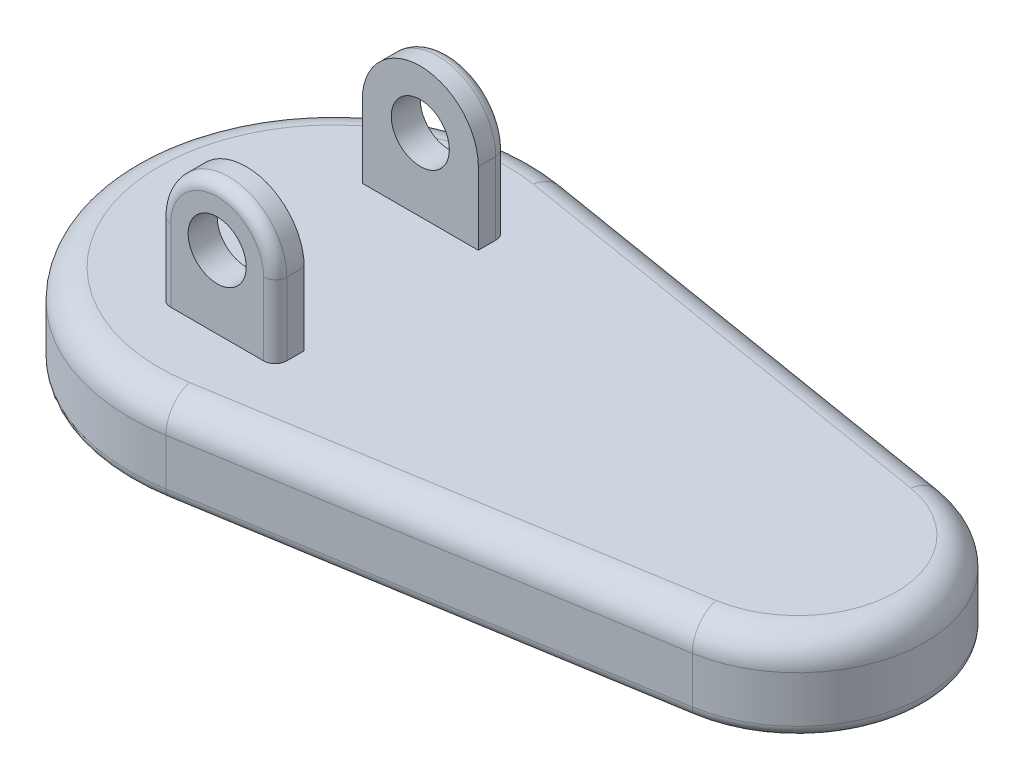
SolidWorks part; units mm, degrees
material "ABS"
ref_plane "Front Plane" through (0, 0, 0) normal (0, 0, 1) x (1, 0, 0)
ref_plane "Top Plane" through (0, 0, 0) normal (0, 1, 0) x (1, 0, 0)
ref_plane "Right Plane" through (0, 0, 0) normal (1, 0, 0) x (0, 0, -1)
sketch "Sketch1" plane through (0, 0, 0) normal (0, 1, 0) x (1, 0, 0)
  line L0 (-94.3769, 43.8592) -> (4.5402, 27.5686)
  line L5 (-94.3769, -43.8592) -> (4.5402, -27.5686)
  arc A0 (4.5402, 27.5686) -> (4.5402, -27.5686) centre (0, 0) cw
  arc A2 (-94.3769, 43.8592) -> (-94.3769, -43.8592) centre (-101.6, 0) ccw
  dimension "D2" = 44.45
  dimension "D3" = 27.94
  dimension "D1" = 101.6
extrude "Boss-Extrude1" add sketch "Sketch1" along normal blind 19.05
sketch "Sketch2" plane through (0, 19.05, 0) normal (0, 1, 0) x (1, 0, 0)
  line L0 (0, 0) -> (-146.05, 0)
  line L1 (-114.3, -19.05) -> (-88.9, -19.05)
  line L2 (-114.3, 25.4) -> (-88.9, 25.4)
  line L3 (-114.3, 25.4) -> (-114.3, 19.05)
  line L4 (-114.3, 19.05) -> (-88.9, 19.05)
  line L5 (-88.9, 25.4) -> (-88.9, 19.05)
  line L6 (-88.9, -25.4) -> (-88.9, -19.05)
  line L7 (-114.3, -25.4) -> (-88.9, -25.4)
  line L8 (-114.3, -25.4) -> (-114.3, -19.05)
  arc A0 (-94.3769, 43.8592) -> (-94.3769, -43.8592) centre (-101.6, 0) ccw construction
  dimension "D1" = 6.35
  dimension "D2" = 25.4
  dimension "D3" = 19.05
  dimension "D4" = 88.9
extrude "Boss-Extrude2" add sketch "Sketch2" along normal blind 38.1 contours L5 L2 L3 L4 | L8 L7 L6 L1
sketch "Sketch3" plane through (0, 0, 25.4) normal (0, 0, 1) x (1, 0, 0)
  line L2 (-114.3, 57.15) -> (-88.9, 57.15) construction
  line L3 (-88.9, 57.15) -> (-88.9, 19.05) construction
  line L4 (-114.3, 57.15) -> (-114.3, 19.05) construction
  circle A0 centre (-101.6, 34.925) radius 6.35
  arc A1 (-114.3, 34.925) -> (-88.9, 34.925) centre (-101.6, 34.925) cw
  point P8 (-101.6, 57.15)
  line M3 (-88.9, 19.05) -> (-88.9, 57.15)
  line M4 (-88.9, 57.15) -> (-114.3, 57.15)
  line M5 (-114.3, 57.15) -> (-114.3, 19.05)
  dimension "D1" = 12.7
  dimension "D3" = 12.7
  dimension "D2" = 15.875
extrude "Cut-Extrude1" cut sketch "Sketch3" against normal through all contours A1 M5 M3 M4 | A0
fillet "Fillet1" radius 6.35 4 edges at (27.94, 19.05, 0) (-44.9183, 19.05, 35.7139) (-146.05, 19.05, 0) (-44.9183, 19.05, -35.7139)
fillet "Fillet2" radius 2.54 4 edges at (-44.9183, 0, -35.7139) (27.94, 0, 0) (-44.9183, 0, 35.7139) (-146.05, 0, 0)
fillet "Fillet3" radius 2.54 6 edges at (-88.9, 26.9875, -25.4) (-114.3, 26.9875, -25.4) (-114.3, 26.9875, 25.4) (-88.9, 26.9875, 25.4) (-101.6, 47.625, -25.4) (-101.6, 47.625, 25.4)
